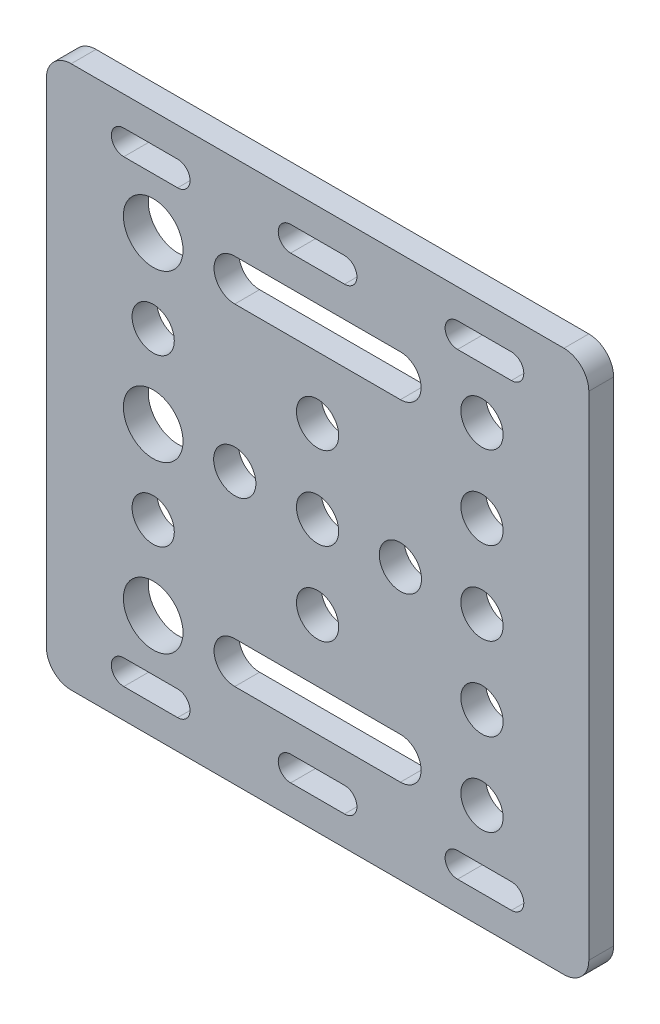
SolidWorks part; units mm, degrees
ref_plane "Спереди" through (0, 0, 0) normal (0, 0, 1) x (1, 0, 0)
ref_plane "Сверху" through (0, 0, 0) normal (0, 1, 0) x (1, 0, 0)
ref_plane "Справа" through (0, 0, 0) normal (1, 0, 0) x (0, 0, -1)
other "Configuration Table"
sketch "Эскиз1" plane through (0, 0, 0) normal (0, 0, 1) x (1, 0, 0)
  line L0 (0, -5.05) -> (65.5, -5.05) construction
  line L5 (3, 0) -> (62.5, 0)
  line L6 (0, -3) -> (0, -62.5)
  line L7 (3, -65.5) -> (62.5, -65.5)
  line L8 (65.5, -3) -> (65.5, -62.5)
  line L9 (0, -12.75) -> (65.5, -12.75) construction
  line L10 (0, -22.75) -> (65.5, -22.75) construction
  line L11 (0, -32.75) -> (65.5, -32.75) construction
  line L12 (0, -42.75) -> (65.5, -42.75) construction
  line L13 (0, -52.75) -> (65.5, -52.75) construction
  line L14 (0, -60.45) -> (65.5, -60.45) construction
  line L15 (9.35, 0) -> (9.35, -65.5) construction
  line L16 (12.9, 0) -> (12.9, -65.5) construction
  line L17 (15.85, 0) -> (15.85, -65.5) construction
  line L18 (22.75, 0) -> (22.75, -65.5) construction
  line L19 (29.5, 0) -> (29.5, -65.5) construction
  line L20 (56.15, 0) -> (56.15, -65.5) construction
  line L21 (49.65, 0) -> (49.65, -65.5) construction
  line L22 (42.75, 0) -> (42.75, -65.5) construction
  line L23 (32.75, 0) -> (32.75, -65.5) construction
  line L24 (36, 0) -> (36, -65.5) construction
  line L25 (52.6, 0) -> (52.6, -65.5) construction
  line L26 (0, 0) -> (0, -5.05)
  line L27 (9.35, -5.05) -> (15.85, -5.05) construction
  line L28 (9.35, -3.55) -> (15.85, -3.55)
  line L29 (9.35, -6.55) -> (15.85, -6.55)
  line L30 (29.5, -5.05) -> (36, -5.05) construction
  line L31 (29.5, -3.55) -> (36, -3.55)
  line L32 (29.5, -6.55) -> (36, -6.55)
  line L33 (49.65, -5.05) -> (56.15, -5.05) construction
  line L34 (49.65, -3.55) -> (56.15, -3.55)
  line L35 (49.65, -6.55) -> (56.15, -6.55)
  line L36 (9.35, -60.45) -> (15.85, -60.45) construction
  line L37 (9.35, -58.95) -> (15.85, -58.95)
  line L38 (9.35, -61.95) -> (15.85, -61.95)
  line L39 (29.5, -60.45) -> (36, -60.45) construction
  line L40 (29.5, -58.95) -> (36, -58.95)
  line L41 (29.5, -61.95) -> (36, -61.95)
  line L42 (49.65, -60.45) -> (56.15, -60.45) construction
  line L43 (49.65, -58.95) -> (56.15, -58.95)
  line L44 (49.65, -61.95) -> (56.15, -61.95)
  line L45 (22.75, -52.75) -> (42.75, -52.75) construction
  line L46 (22.75, -50.25) -> (42.75, -50.25)
  line L47 (22.75, -55.25) -> (42.75, -55.25)
  line L48 (22.75, -12.75) -> (42.75, -12.75) construction
  line L49 (22.75, -10.25) -> (42.75, -10.25)
  line L50 (22.75, -15.25) -> (42.75, -15.25)
  circle A0 centre (52.6, -12.75) radius 2.55
  circle A1 centre (52.6, -22.75) radius 2.55
  circle A2 centre (52.6, -32.75) radius 2.55
  circle A3 centre (52.6, -42.75) radius 2.55
  circle A4 centre (52.6, -52.75) radius 2.55
  circle A5 centre (12.9, -12.75) radius 3.6
  circle A6 centre (12.9, -22.75) radius 2.55
  circle A7 centre (12.9, -32.75) radius 3.6
  circle A8 centre (12.9, -42.75) radius 2.55
  circle A9 centre (12.9, -52.75) radius 3.6
  circle A10 centre (22.75, -32.75) radius 2.55
  circle A11 centre (32.75, -32.75) radius 2.55
  circle A12 centre (42.75, -32.75) radius 2.55
  circle A13 centre (32.75, -22.75) radius 2.55
  circle A14 centre (32.75, -42.75) radius 2.55
  arc A15 (9.35, -3.55) -> (9.35, -6.55) centre (9.35, -5.05) ccw
  arc A16 (15.85, -6.55) -> (15.85, -3.55) centre (15.85, -5.05) ccw
  arc A17 (29.5, -3.55) -> (29.5, -6.55) centre (29.5, -5.05) ccw
  arc A18 (36, -6.55) -> (36, -3.55) centre (36, -5.05) ccw
  arc A19 (49.65, -3.55) -> (49.65, -6.55) centre (49.65, -5.05) ccw
  arc A20 (56.15, -6.55) -> (56.15, -3.55) centre (56.15, -5.05) ccw
  arc A21 (9.35, -58.95) -> (9.35, -61.95) centre (9.35, -60.45) ccw
  arc A22 (15.85, -61.95) -> (15.85, -58.95) centre (15.85, -60.45) ccw
  arc A23 (29.5, -58.95) -> (29.5, -61.95) centre (29.5, -60.45) ccw
  arc A24 (36, -61.95) -> (36, -58.95) centre (36, -60.45) ccw
  arc A25 (49.65, -58.95) -> (49.65, -61.95) centre (49.65, -60.45) ccw
  arc A26 (56.15, -61.95) -> (56.15, -58.95) centre (56.15, -60.45) ccw
  arc A27 (22.75, -50.25) -> (22.75, -55.25) centre (22.75, -52.75) ccw
  arc A28 (42.75, -55.25) -> (42.75, -50.25) centre (42.75, -52.75) ccw
  arc A29 (22.75, -10.25) -> (22.75, -15.25) centre (22.75, -12.75) ccw
  arc A30 (42.75, -15.25) -> (42.75, -10.25) centre (42.75, -12.75) ccw
  arc A31 (3, 0) -> (0, -3) centre (3, -3) ccw
  arc A32 (0, -62.5) -> (3, -65.5) centre (3, -62.5) ccw
  arc A33 (62.5, -65.5) -> (65.5, -62.5) centre (62.5, -62.5) ccw
  arc A34 (62.5, 0) -> (65.5, -3) centre (62.5, -3) cw
  point P70 (12.6, -5.05)
  point P75 (32.75, -5.05)
  point P86 (52.9, -5.05)
  point P93 (12.6, -60.45)
  point P100 (32.75, -60.45)
  point P107 (52.9, -60.45)
  point P114 (32.75, -52.75)
  point P121 (32.75, -12.75)
  point P128 (0, 0)
  point P129 (0, 0)
  point P136 (65.5, -65.5)
  point P139 (65.5, 0)
  point P140 (65.5, -32.75)
  point P141 (65.5, -22.75)
  point P142 (65.5, -32.75)
  point P143 (65.5, -12.75)
  point P144 (65.5, -42.75)
  point P145 (0, 0)
  point P146 (65.5, -52.75)
  point P147 (65.5, -60.45)
  point P148 (56.15, -65.5)
  point P149 (49.65, -65.5)
  point P150 (42.75, -65.5)
  point P151 (36, -65.5)
  point P152 (29.5, -65.5)
  point P153 (32.75, -65.5)
  point P154 (0, 0)
  point P155 (15.85, -65.5)
  point P156 (0, -60.45)
  point P157 (0, -52.75)
  point P158 (0, -42.75)
  point P159 (0, -32.75)
  point P160 (0, 0)
  point P161 (0, -22.75)
  point P162 (0, -12.75)
  dimension "D21" = 5.1
  dimension "D22" = 7.2
  dimension "D23" = 3
  dimension "D31" = 3
  dimension "D1" = 65.5
  dimension "D2" = 65.5
  dimension "D3" = 22.75
  dimension "D4" = 15.85
  dimension "D5" = 5.05
  dimension "D6" = 12.75
  dimension "D7" = 32.75
  dimension "D8" = 42.75
  dimension "D9" = 52.75
  dimension "D10" = 60.45
  dimension "D11" = 9.35
  dimension "D12" = 12.9
  dimension "D13" = 22.75
  dimension "D14" = 29.5
  dimension "D15" = 32.75
  dimension "D16" = 36
  dimension "D17" = 42.75
  dimension "D18" = 49.65
  dimension "D19" = 52.6
  dimension "D20" = 56.15
  dimension "D24" = 3
  dimension "D25" = 3
  dimension "D26" = 3
  dimension "D27" = 3
  dimension "D28" = 3
  dimension "D29" = 5
  dimension "D30" = 5
extrude "Бобышка-Вытянуть1" add sketch "Эскиз1" along normal blind 3 contours A34 L5 A31 L6 A32 L7 A33 L8 A30 L50 A29 L49 A28 L47 A27 L46 A26 L44 A25 L43 A24 L41 A23 L40 A22 L38 A21 L37 A20 L35 A19 L34 A18 L32 A17 L31 A16 L29 A15 L28 A14
